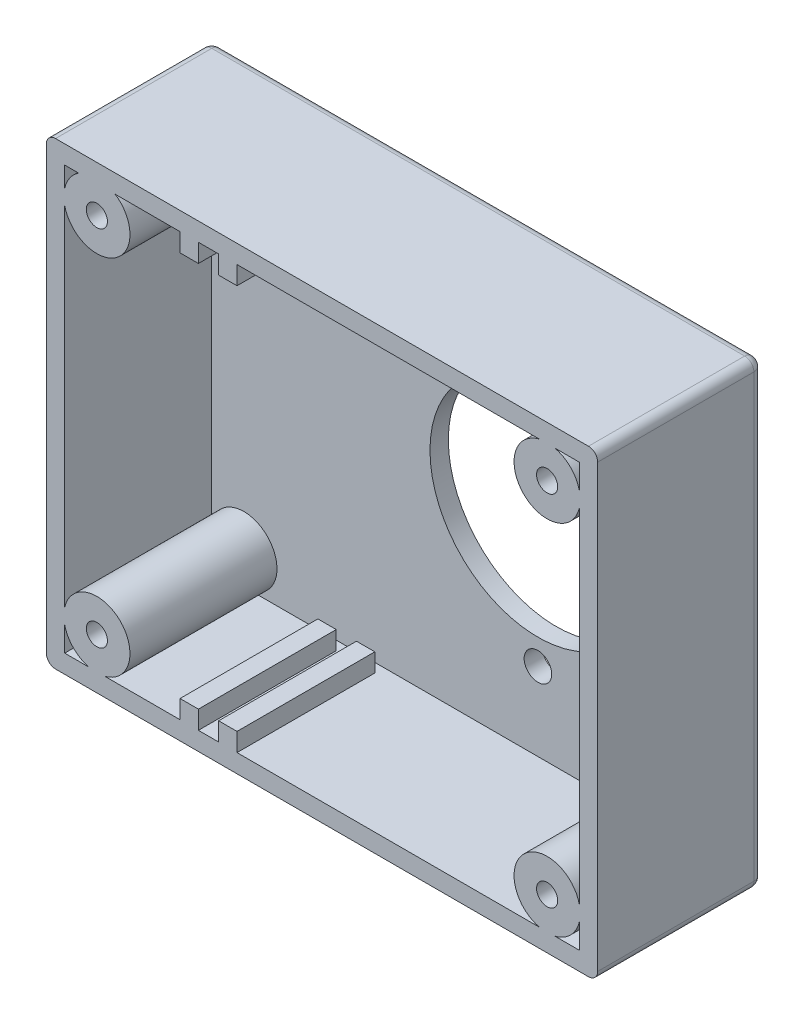
SolidWorks part; units mm, degrees
ref_plane "Front Plane" through (0, 0, 0) normal (0, 0, 1) x (1, 0, 0)
ref_plane "Top Plane" through (0, 0, 0) normal (0, 1, 0) x (1, 0, 0)
ref_plane "Right Plane" through (0, 0, 0) normal (1, 0, 0) x (0, 0, -1)
sketch "Sketch2" plane through (0, 0, 0) normal (0, 0, 1) x (1, 0, 0)
  line L1 (-30, 25) -> (30, 25)
  line L2 (-30, 25) -> (-30, -25)
  line L3 (-30, -25) -> (30, -25)
  line L4 (30, 25) -> (30, -25)
  line L5 (-30, 25) -> (30, -25) construction
  line L6 (-30, -25) -> (30, 25) construction
  point P0 (0, 0)
  dimension "D1" = 50
  dimension "D2" = 60
extrude "Boss-Extrude1" add sketch "Sketch2" along normal mid plane 18
shell "Shell1" thickness 2
sketch "Sketch3" plane through (0, 0, -7) normal (0, 0, 1) x (1, 0, 0)
  line L0 (-37.716, 0) -> (37.716, 0) construction
  line L1 (0, -27.2393) -> (0, 27.2393) construction
sketch "Sketch6" plane through (0, 0, -9) normal (0, 0, -1) x (-1, 0, 0)
  line L0 (37.716, 0) -> (-37.716, 0) construction
  line L1 (-7.5, 32.9491) -> (-7.5, -32.9491) construction
  line L2 (-28, -23) -> (-28, 23) construction
  circle A0 centre (-7.5, 0) radius 11.75
  circle A1 centre (-7.5, 14.5) radius 1.5
  circle A2 centre (-7.5, -14.5) radius 1.5
  dimension "D1" = 20.5
  dimension "D2" = 23.5
  dimension "D3" = 3
  dimension "D4" = 14.5
  dimension "D5" = 29
extrude "Cut-Extrude3" cut sketch "Sketch6" against normal blind 18 contours A2 | A0 | A1
sketch "Sketch8" plane through (0, 0, -7) normal (0, 0, 1) x (1, 0, 0)
  line L3 (-32.7818, 20) -> (40.7264, 20) construction
  line L4 (-24.5, 29.1859) -> (-24.5, -30.6075) construction
  circle A0 centre (-24.5, 20) radius 3.6
  dimension "D1" = 7.2
extrude "Boss-Extrude7" add sketch "Sketch8" along normal through all
sketch "Sketch10" plane through (0, 0, -7) normal (0, 0, 1) x (1, 0, 0)
  line L0 (-30, -25) -> (30, -25) construction
  line L1 (-30, 25) -> (-30, -25) construction
  line L2 (36.2942, -19.5) -> (-44.7405, -19.5) construction
  line L3 (24.5, -27.5969) -> (24.5, 29.7712) construction
  line L4 (-39.9737, 0) -> (47.7511, 0) construction
  line L5 (0, 27.2393) -> (0, -30.6075) construction
  circle A0 centre (24.5, -19.5) radius 3.6
  circle A1 centre (24.5, 19.5) radius 3.6
  circle A2 centre (-24.5, -19.5) radius 3.6
  arc A3 (-28, 19.1574) -> (-22.51, 23) centre (-24.5, 20) ccw construction
  dimension "D1" = 5.5
  dimension "D2" = 5.5
extrude "Boss-Extrude8" add sketch "Sketch10" along normal through all
sketch "Sketch11" plane through (0, 0, 9) normal (0, 0, 1) x (1, 0, 0)
  circle A0 centre (-24.5, 20) radius 1.15
  circle A1 centre (24.5, 19.5) radius 1.15
  circle A2 centre (24.5, -19.5) radius 1.15
  circle A3 centre (-24.5, -19.5) radius 1.15
  arc A4 (-28, 19.1574) -> (-22.51, 23) centre (-24.5, 20) ccw construction
  arc A5 (23.6574, 23) -> (28, 18.6574) centre (24.5, 19.5) ccw construction
  arc A7 (-23.6574, -23) -> (-28, -18.6574) centre (-24.5, -19.5) ccw construction
  arc A8 (28, -18.6574) -> (23.6574, -23) centre (24.5, -19.5) ccw construction
  dimension "D1" = 2.3
extrude "Cut-Extrude4" cut sketch "Sketch11" against normal blind 17
sketch "Sketch12" plane through (0, 0, 9) normal (0, 0, 1) x (1, 0, 0)
  line L0 (-9.25, 28.0151) -> (-9.25, -30.6075) construction
  line L1 (-4.25, 28.0151) -> (-4.25, -30.6075) construction
  line L2 (-23.6574, -23) -> (23.6574, -23) construction
  line L3 (-9.25, -23) -> (-11.25, -23)
  line L4 (-9.25, -23) -> (-9.25, -21)
  line L5 (-9.25, -21) -> (-11.25, -21)
  line L6 (-11.25, -23) -> (-11.25, -21)
  line L7 (-13.45, -21) -> (-15.45, -21)
  line L8 (-13.45, -23) -> (-13.45, -21)
  line L9 (-15.45, -23) -> (-15.45, -21)
  line L10 (-13.45, -23) -> (-15.45, -23)
  line L11 (-36.2132, 0) -> (34.577, 0) construction
  line L12 (-37.716, 0) -> (37.716, 0) construction
  line L13 (-13.45, 23) -> (-15.45, 23)
  line L14 (-15.45, 23) -> (-15.45, 21)
  line L15 (-13.45, 23) -> (-13.45, 21)
  line L16 (-13.45, 21) -> (-15.45, 21)
  line L17 (-11.25, 23) -> (-11.25, 21)
  line L18 (-9.25, 21) -> (-11.25, 21)
  line L19 (-9.25, 23) -> (-9.25, 21)
  line L20 (-9.25, 23) -> (-11.25, 23)
  circle A0 centre (7.5, 0) radius 11.75 construction
  dimension "D1" = 5
  dimension "D2" = 2
  dimension "D3" = 2
  dimension "D4" = 2.2
  dimension "D5" = 2
extrude "Boss-Extrude13" add sketch "Sketch12" against normal blind 15
fillet "Fillet3" radius 1 8 edges at (-30, 25, 0) (-30, 0, -9) (0, 25, -9) (30, 25, 0) (30, 0, -9) (0, -25, -9) (-30, -25, 0) (30, -25, 0)
